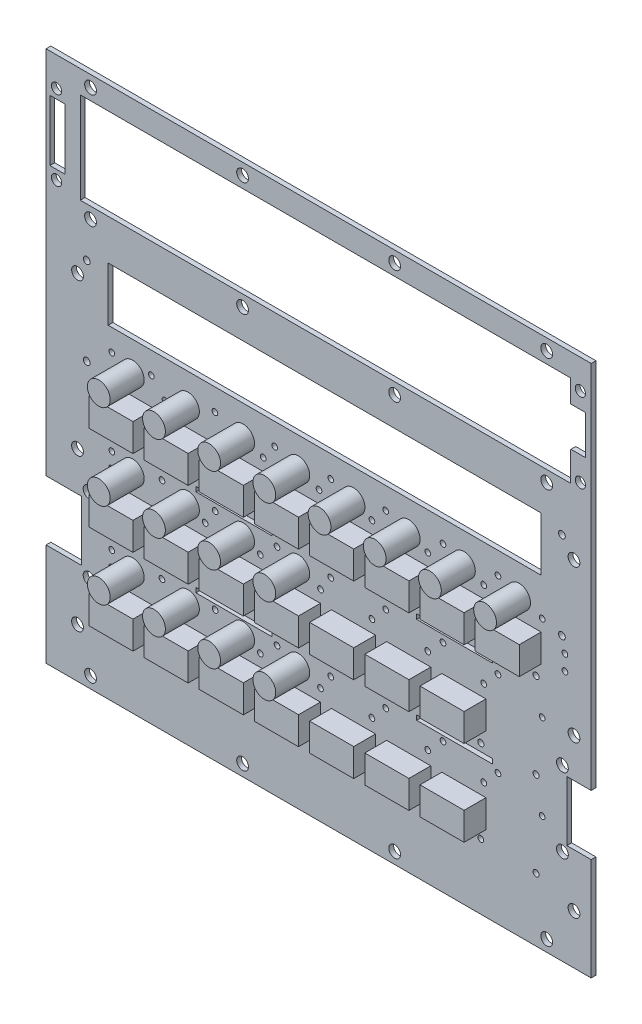
SolidWorks part; units mm, degrees
ref_plane "Front Plane" through (0, 0, 0) normal (0, 0, 1) x (1, 0, 0)
ref_plane "Top Plane" through (0, 0, 0) normal (0, 1, 0) x (1, 0, 0)
ref_plane "Right Plane" through (0, 0, 0) normal (1, 0, 0) x (0, 0, -1)
sketch "Sketch1" plane through (0, 0, 0) normal (0, 0, 1) x (1, 0, 0)
  line L0 (0, 0) -> (182.118, 0)
  line L1 (182.118, 0) -> (182.118, 34.2468)
  line L2 (182.118, 34.2468) -> (173.9875, 34.2468)
  line L3 (173.9875, 34.2468) -> (173.9875, 54.2468)
  line L4 (173.9875, 54.2468) -> (182.118, 54.2468)
  line L5 (182.118, 54.2468) -> (182.118, 177.8)
  line L6 (182.118, 177.8) -> (0, 177.8)
  line L7 (0, 177.8) -> (0, 54.2468)
  line L8 (0, 54.2468) -> (11.8694, 54.2468)
  line L9 (11.8694, 54.2468) -> (11.8694, 34.2468)
  line L10 (11.8694, 34.2468) -> (0, 34.2468)
  line L11 (0, 34.2468) -> (0, 0)
  line L12 (20.7391, 108.1786) -> (20.7391, 126.1796)
  line L13 (20.7391, 126.1796) -> (165.3007, 126.1796)
  line L14 (165.3007, 126.1796) -> (165.3007, 108.1786)
  line L15 (165.3007, 108.1786) -> (20.7391, 108.1786)
  line L16 (1.27, 144.653) -> (1.27, 164.973)
  line L17 (1.27, 164.973) -> (6.35, 164.973)
  line L18 (6.35, 164.973) -> (6.35, 144.653)
  line L19 (6.35, 144.653) -> (1.27, 144.653)
  line L20 (12.7, 170.18) -> (175.26, 170.18)
  line L21 (175.26, 170.18) -> (175.26, 162.6616)
  line L22 (175.26, 162.6616) -> (180.086, 162.6616)
  line L23 (180.086, 162.6616) -> (180.2892, 162.4584)
  line L24 (180.2892, 162.4584) -> (180.2892, 149.606)
  line L25 (180.2892, 149.606) -> (175.3616, 149.606)
  line L26 (175.3616, 149.606) -> (175.26, 149.5044)
  line L27 (175.26, 149.5044) -> (175.26, 139.7)
  line L28 (175.26, 139.7) -> (12.7, 139.7)
  line L29 (12.7, 139.7) -> (11.43, 139.7)
  line L30 (11.43, 139.7) -> (11.43, 170.18)
  line L31 (11.43, 170.18) -> (12.7, 170.18)
  line L32 (50.0634, 45.4152) -> (50.0634, 47.0027)
  line L33 (50.0634, 47.0027) -> (75.4634, 47.0027)
  line L34 (75.4634, 47.0027) -> (75.4634, 45.4152)
  line L35 (75.4634, 45.4152) -> (50.0634, 45.4152)
  line L36 (123.8134, 45.4152) -> (123.8134, 47.0027)
  line L37 (123.8134, 47.0027) -> (149.2134, 47.0027)
  line L38 (149.2134, 47.0027) -> (149.2134, 45.4152)
  line L39 (149.2134, 45.4152) -> (123.8134, 45.4152)
  line L40 (123.8134, 74.6252) -> (123.8134, 76.2127)
  line L41 (123.8134, 76.2127) -> (149.2134, 76.2127)
  line L42 (149.2134, 76.2127) -> (149.2134, 74.6252)
  line L43 (149.2134, 74.6252) -> (123.8134, 74.6252)
  line L44 (50.0634, 74.6252) -> (50.0634, 76.2127)
  line L45 (50.0634, 76.2127) -> (75.4634, 76.2127)
  line L46 (75.4634, 76.2127) -> (75.4634, 74.6252)
  line L47 (75.4634, 74.6252) -> (50.0634, 74.6252)
extrude "BOARD" add sketch "Sketch1" along normal blind 1.5921 separate body
ref_plane "Plane1" through (0, 0, 1.5921) normal (0, 0, 1) x (1, 0, 0)
sketch "Sketch11" plane through (0, 0, 1.5921) normal (0, 0, 1) x (1, 0, 0)
  circle A0 centre (84.2812, 41.1988) radius 3.81
extrude "LED-KINGBRIGHT_3P_2P54-10" add sketch "Sketch11" along normal blind 11.3538 separate body
sketch "Sketch12" plane through (0, 0, 1.5921) normal (0, 0, 1) x (1, 0, 0)
  circle A0 centre (65.8437, 41.1988) radius 3.81
extrude "LED-KINGBRIGHT_3P_2P54-11" add sketch "Sketch12" along normal blind 11.3538 separate body
sketch "Sketch13" plane through (0, 0, 1.5921) normal (0, 0, 1) x (1, 0, 0)
  circle A0 centre (47.4062, 41.1988) radius 3.81
extrude "LED-KINGBRIGHT_3P_2P54-12" add sketch "Sketch13" along normal blind 11.3538 separate body
sketch "Sketch14" plane through (0, 0, 1.5921) normal (0, 0, 1) x (1, 0, 0)
  circle A0 centre (28.9687, 41.1988) radius 3.81
extrude "LED-KINGBRIGHT_3P_2P54-13" add sketch "Sketch14" along normal blind 11.3538 separate body
sketch "Sketch15" plane through (0, 0, 1.5921) normal (0, 0, 1) x (1, 0, 0)
  circle A0 centre (84.2812, 69.7738) radius 3.81
extrude "LED-KINGBRIGHT_3P_2P54-14" add sketch "Sketch15" along normal blind 11.3538 separate body
sketch "Sketch16" plane through (0, 0, 1.5921) normal (0, 0, 1) x (1, 0, 0)
  circle A0 centre (65.8437, 69.7738) radius 3.81
extrude "LED-KINGBRIGHT_3P_2P54-15" add sketch "Sketch16" along normal blind 11.3538 separate body
sketch "Sketch17" plane through (0, 0, 1.5921) normal (0, 0, 1) x (1, 0, 0)
  circle A0 centre (47.4062, 69.7738) radius 3.81
extrude "LED-KINGBRIGHT_3P_2P54-16" add sketch "Sketch17" along normal blind 11.3538 separate body
sketch "Sketch18" plane through (0, 0, 1.5921) normal (0, 0, 1) x (1, 0, 0)
  circle A0 centre (28.9687, 69.7738) radius 3.81
extrude "LED-KINGBRIGHT_3P_2P54-17" add sketch "Sketch18" along normal blind 11.3538 separate body
sketch "Sketch19" plane through (0, 0, 1.5921) normal (0, 0, 1) x (1, 0, 0)
  circle A0 centre (158.0312, 98.3488) radius 3.81
extrude "LED-KINGBRIGHT_3P_2P54-18" add sketch "Sketch19" along normal blind 11.3538 separate body
sketch "Sketch20" plane through (0, 0, 1.5921) normal (0, 0, 1) x (1, 0, 0)
  circle A0 centre (139.5937, 98.3488) radius 3.81
extrude "LED-KINGBRIGHT_3P_2P54-19" add sketch "Sketch20" along normal blind 11.3538 separate body
sketch "Sketch21" plane through (0, 0, 1.5921) normal (0, 0, 1) x (1, 0, 0)
  circle A0 centre (121.1562, 98.3488) radius 3.81
extrude "LED-KINGBRIGHT_3P_2P54-20" add sketch "Sketch21" along normal blind 11.3538 separate body
sketch "Sketch22" plane through (0, 0, 1.5921) normal (0, 0, 1) x (1, 0, 0)
  circle A0 centre (102.7187, 98.3488) radius 3.81
extrude "LED-KINGBRIGHT_3P_2P54-21" add sketch "Sketch22" along normal blind 11.3538 separate body
sketch "Sketch23" plane through (0, 0, 1.5921) normal (0, 0, 1) x (1, 0, 0)
  circle A0 centre (84.2812, 98.3488) radius 3.81
extrude "LED-KINGBRIGHT_3P_2P54-22" add sketch "Sketch23" along normal blind 11.3538 separate body
sketch "Sketch24" plane through (0, 0, 1.5921) normal (0, 0, 1) x (1, 0, 0)
  circle A0 centre (65.8437, 98.3488) radius 3.81
extrude "LED-KINGBRIGHT_3P_2P54-23" add sketch "Sketch24" along normal blind 11.3538 separate body
sketch "Sketch25" plane through (0, 0, 1.5921) normal (0, 0, 1) x (1, 0, 0)
  circle A0 centre (47.4062, 98.3488) radius 3.81
extrude "LED-KINGBRIGHT_3P_2P54-24" add sketch "Sketch25" along normal blind 11.3538 separate body
sketch "Sketch26" plane through (0, 0, 1.5921) normal (0, 0, 1) x (1, 0, 0)
  circle A0 centre (28.9687, 98.3488) radius 3.81
extrude "LED-KINGBRIGHT_3P_2P54-25" add sketch "Sketch26" along normal blind 11.3538 separate body
sketch "Sketch29" plane through (0, 0, 1.5921) normal (0, 0, 1) x (1, 0, 0)
  line L0 (132.2277, 25.3238) -> (132.2277, 34.5948)
  line L1 (132.2277, 34.5948) -> (146.9597, 34.5948)
  line L2 (146.9597, 34.5948) -> (146.9597, 25.3238)
  line L3 (146.9597, 25.3238) -> (132.2277, 25.3238)
extrude "SWITCH-MCDTS2-3" add sketch "Sketch29" along normal blind 7.3 separate body
sketch "Sketch30" plane through (0, 0, 1.5921) normal (0, 0, 1) x (1, 0, 0)
  line L0 (113.7902, 25.3238) -> (113.7902, 34.5948)
  line L1 (113.7902, 34.5948) -> (128.5222, 34.5948)
  line L2 (128.5222, 34.5948) -> (128.5222, 25.3238)
  line L3 (128.5222, 25.3238) -> (113.7902, 25.3238)
extrude "SWITCH-MCDTS2-4" add sketch "Sketch30" along normal blind 7.3 separate body
sketch "Sketch31" plane through (0, 0, 1.5921) normal (0, 0, 1) x (1, 0, 0)
  line L0 (95.3527, 25.3238) -> (95.3527, 34.5948)
  line L1 (95.3527, 34.5948) -> (110.0847, 34.5948)
  line L2 (110.0847, 34.5948) -> (110.0847, 25.3238)
  line L3 (110.0847, 25.3238) -> (95.3527, 25.3238)
extrude "SWITCH-MCDTS2-5" add sketch "Sketch31" along normal blind 7.3 separate body
sketch "Sketch32" plane through (0, 0, 1.5921) normal (0, 0, 1) x (1, 0, 0)
  line L0 (76.9152, 25.3238) -> (76.9152, 34.5948)
  line L1 (76.9152, 34.5948) -> (91.6472, 34.5948)
  line L2 (91.6472, 34.5948) -> (91.6472, 25.3238)
  line L3 (91.6472, 25.3238) -> (76.9152, 25.3238)
extrude "SWITCH-MCDTS2-6" add sketch "Sketch32" along normal blind 7.3 separate body
sketch "Sketch33" plane through (0, 0, 1.5921) normal (0, 0, 1) x (1, 0, 0)
  line L0 (58.4777, 25.3238) -> (58.4777, 34.5948)
  line L1 (58.4777, 34.5948) -> (73.2097, 34.5948)
  line L2 (73.2097, 34.5948) -> (73.2097, 25.3238)
  line L3 (73.2097, 25.3238) -> (58.4777, 25.3238)
extrude "SWITCH-MCDTS2-7" add sketch "Sketch33" along normal blind 7.3 separate body
sketch "Sketch34" plane through (0, 0, 1.5921) normal (0, 0, 1) x (1, 0, 0)
  line L0 (40.0402, 25.3238) -> (40.0402, 34.5948)
  line L1 (40.0402, 34.5948) -> (54.7722, 34.5948)
  line L2 (54.7722, 34.5948) -> (54.7722, 25.3238)
  line L3 (54.7722, 25.3238) -> (40.0402, 25.3238)
extrude "SWITCH-MCDTS2-8" add sketch "Sketch34" along normal blind 7.3 separate body
sketch "Sketch35" plane through (0, 0, 1.5921) normal (0, 0, 1) x (1, 0, 0)
  line L0 (21.6027, 25.3238) -> (21.6027, 34.5948)
  line L1 (21.6027, 34.5948) -> (36.3347, 34.5948)
  line L2 (36.3347, 34.5948) -> (36.3347, 25.3238)
  line L3 (36.3347, 25.3238) -> (21.6027, 25.3238)
extrude "SWITCH-MCDTS2-9" add sketch "Sketch35" along normal blind 7.3 separate body
sketch "Sketch36" plane through (0, 0, 1.5921) normal (0, 0, 1) x (1, 0, 0)
  line L0 (132.2277, 53.8988) -> (132.2277, 63.1698)
  line L1 (132.2277, 63.1698) -> (146.9597, 63.1698)
  line L2 (146.9597, 63.1698) -> (146.9597, 53.8988)
  line L3 (146.9597, 53.8988) -> (132.2277, 53.8988)
extrude "SWITCH-MCDTS2-10" add sketch "Sketch36" along normal blind 7.3 separate body
sketch "Sketch37" plane through (0, 0, 1.5921) normal (0, 0, 1) x (1, 0, 0)
  line L0 (113.7902, 53.8988) -> (113.7902, 63.1698)
  line L1 (113.7902, 63.1698) -> (128.5222, 63.1698)
  line L2 (128.5222, 63.1698) -> (128.5222, 53.8988)
  line L3 (128.5222, 53.8988) -> (113.7902, 53.8988)
extrude "SWITCH-MCDTS2-11" add sketch "Sketch37" along normal blind 7.3 separate body
sketch "Sketch38" plane through (0, 0, 1.5921) normal (0, 0, 1) x (1, 0, 0)
  line L0 (95.3527, 53.8988) -> (95.3527, 63.1698)
  line L1 (95.3527, 63.1698) -> (110.0847, 63.1698)
  line L2 (110.0847, 63.1698) -> (110.0847, 53.8988)
  line L3 (110.0847, 53.8988) -> (95.3527, 53.8988)
extrude "SWITCH-MCDTS2-12" add sketch "Sketch38" along normal blind 7.3 separate body
sketch "Sketch39" plane through (0, 0, 1.5921) normal (0, 0, 1) x (1, 0, 0)
  line L0 (76.9152, 53.8988) -> (76.9152, 63.1698)
  line L1 (76.9152, 63.1698) -> (91.6472, 63.1698)
  line L2 (91.6472, 63.1698) -> (91.6472, 53.8988)
  line L3 (91.6472, 53.8988) -> (76.9152, 53.8988)
extrude "SWITCH-MCDTS2-13" add sketch "Sketch39" along normal blind 7.3 separate body
sketch "Sketch40" plane through (0, 0, 1.5921) normal (0, 0, 1) x (1, 0, 0)
  line L0 (58.4777, 53.8988) -> (58.4777, 63.1698)
  line L1 (58.4777, 63.1698) -> (73.2097, 63.1698)
  line L2 (73.2097, 63.1698) -> (73.2097, 53.8988)
  line L3 (73.2097, 53.8988) -> (58.4777, 53.8988)
extrude "SWITCH-MCDTS2-14" add sketch "Sketch40" along normal blind 7.3 separate body
sketch "Sketch41" plane through (0, 0, 1.5921) normal (0, 0, 1) x (1, 0, 0)
  line L0 (40.0402, 53.8988) -> (40.0402, 63.1698)
  line L1 (40.0402, 63.1698) -> (54.7722, 63.1698)
  line L2 (54.7722, 63.1698) -> (54.7722, 53.8988)
  line L3 (54.7722, 53.8988) -> (40.0402, 53.8988)
extrude "SWITCH-MCDTS2-15" add sketch "Sketch41" along normal blind 7.3 separate body
sketch "Sketch42" plane through (0, 0, 1.5921) normal (0, 0, 1) x (1, 0, 0)
  line L0 (21.6027, 53.8988) -> (21.6027, 63.1698)
  line L1 (21.6027, 63.1698) -> (36.3347, 63.1698)
  line L2 (36.3347, 63.1698) -> (36.3347, 53.8988)
  line L3 (36.3347, 53.8988) -> (21.6027, 53.8988)
extrude "SWITCH-MCDTS2-16" add sketch "Sketch42" along normal blind 7.3 separate body
sketch "Sketch43" plane through (0, 0, 1.5921) normal (0, 0, 1) x (1, 0, 0)
  line L0 (150.6652, 82.4738) -> (150.6652, 91.7448)
  line L1 (150.6652, 91.7448) -> (165.3972, 91.7448)
  line L2 (165.3972, 91.7448) -> (165.3972, 82.4738)
  line L3 (165.3972, 82.4738) -> (150.6652, 82.4738)
extrude "SWITCH-MCDTS2-17" add sketch "Sketch43" along normal blind 7.3 separate body
sketch "Sketch44" plane through (0, 0, 1.5921) normal (0, 0, 1) x (1, 0, 0)
  line L0 (132.2277, 82.4738) -> (132.2277, 91.7448)
  line L1 (132.2277, 91.7448) -> (146.9597, 91.7448)
  line L2 (146.9597, 91.7448) -> (146.9597, 82.4738)
  line L3 (146.9597, 82.4738) -> (132.2277, 82.4738)
extrude "SWITCH-MCDTS2-18" add sketch "Sketch44" along normal blind 7.3 separate body
sketch "Sketch45" plane through (0, 0, 1.5921) normal (0, 0, 1) x (1, 0, 0)
  line L0 (113.7902, 82.4738) -> (113.7902, 91.7448)
  line L1 (113.7902, 91.7448) -> (128.5222, 91.7448)
  line L2 (128.5222, 91.7448) -> (128.5222, 82.4738)
  line L3 (128.5222, 82.4738) -> (113.7902, 82.4738)
extrude "SWITCH-MCDTS2-19" add sketch "Sketch45" along normal blind 7.3 separate body
sketch "Sketch46" plane through (0, 0, 1.5921) normal (0, 0, 1) x (1, 0, 0)
  line L0 (95.3527, 82.4738) -> (95.3527, 91.7448)
  line L1 (95.3527, 91.7448) -> (110.0847, 91.7448)
  line L2 (110.0847, 91.7448) -> (110.0847, 82.4738)
  line L3 (110.0847, 82.4738) -> (95.3527, 82.4738)
extrude "SWITCH-MCDTS2-20" add sketch "Sketch46" along normal blind 7.3 separate body
sketch "Sketch47" plane through (0, 0, 1.5921) normal (0, 0, 1) x (1, 0, 0)
  line L0 (76.9152, 82.4738) -> (76.9152, 91.7448)
  line L1 (76.9152, 91.7448) -> (91.6472, 91.7448)
  line L2 (91.6472, 91.7448) -> (91.6472, 82.4738)
  line L3 (91.6472, 82.4738) -> (76.9152, 82.4738)
extrude "SWITCH-MCDTS2-21" add sketch "Sketch47" along normal blind 7.3 separate body
sketch "Sketch48" plane through (0, 0, 1.5921) normal (0, 0, 1) x (1, 0, 0)
  line L0 (58.4777, 82.4738) -> (58.4777, 91.7448)
  line L1 (58.4777, 91.7448) -> (73.2097, 91.7448)
  line L2 (73.2097, 91.7448) -> (73.2097, 82.4738)
  line L3 (73.2097, 82.4738) -> (58.4777, 82.4738)
extrude "SWITCH-MCDTS2-22" add sketch "Sketch48" along normal blind 7.3 separate body
sketch "Sketch49" plane through (0, 0, 1.5921) normal (0, 0, 1) x (1, 0, 0)
  line L0 (40.0402, 82.4738) -> (40.0402, 91.7448)
  line L1 (40.0402, 91.7448) -> (54.7722, 91.7448)
  line L2 (54.7722, 91.7448) -> (54.7722, 82.4738)
  line L3 (54.7722, 82.4738) -> (40.0402, 82.4738)
extrude "SWITCH-MCDTS2-23" add sketch "Sketch49" along normal blind 7.3 separate body
sketch "Sketch50" plane through (0, 0, 1.5921) normal (0, 0, 1) x (1, 0, 0)
  line L0 (21.6027, 82.4738) -> (21.6027, 91.7448)
  line L1 (21.6027, 91.7448) -> (36.3347, 91.7448)
  line L2 (36.3347, 91.7448) -> (36.3347, 82.4738)
  line L3 (36.3347, 82.4738) -> (21.6027, 82.4738)
extrude "SWITCH-MCDTS2-24" add sketch "Sketch50" along normal blind 7.3 separate body
sketch "Sketch56" plane through (0, 0, 1.5921) normal (0, 0, 1) x (1, 0, 0)
  circle B0 centre (163.703, 21.1074) radius 1.016
  circle B1 centre (163.703, 49.6824) radius 1.016
  circle B2 centre (145.2626, 21.8186) radius 0.9652
  circle B3 centre (126.8476, 21.6154) radius 0.9652
  circle B4 centre (108.4072, 21.7424) radius 0.9652
  circle B5 centre (89.9668, 21.844) radius 0.9652
  circle B6 centre (71.5264, 20.7772) radius 0.9652
  circle B7 centre (53.086, 21.1582) radius 0.9652
  circle B8 centre (34.6472, 21.1328) radius 1.016
  circle B9 centre (145.2626, 49.5554) radius 1.016
  circle B10 centre (126.8222, 49.3522) radius 1.016
  circle B11 centre (108.3818, 49.1236) radius 1.016
  circle B12 centre (89.9414, 49.6824) radius 1.016
  circle B13 centre (71.501, 49.1998) radius 1.016
  circle B14 centre (53.0606, 49.1998) radius 1.016
  circle B15 centre (34.6202, 49.276) radius 1.016
  circle B16 centre (163.703, 78.2574) radius 1.016
  circle B17 centre (145.2626, 77.7748) radius 1.016
  circle B18 centre (126.746, 78.3336) radius 1.016
  circle B19 centre (108.3818, 78.74) radius 1.016
  circle B20 centre (89.9414, 78.3336) radius 1.016
  circle B21 centre (71.501, 78.2574) radius 1.016
  circle B22 centre (53.0606, 78.4098) radius 1.016
  circle B23 centre (34.6202, 78.0542) radius 1.016
  circle B24 centre (91.694, 38.6588) radius 0.9525
  circle B25 centre (77.1652, 43.7388) radius 0.9525
  circle B26 centre (71.5772, 38.6588) radius 0.9525
  circle B27 centre (56.4896, 43.7388) radius 0.9525
  circle B28 centre (38.735, 43.7388) radius 0.9525
  circle B29 centre (21.8948, 38.6588) radius 0.9525
  circle B30 centre (21.971, 43.7388) radius 0.9525
  circle B31 centre (77.1652, 72.3138) radius 0.9525
  circle B32 centre (91.694, 67.2338) radius 0.9525
  circle B33 centre (71.5772, 67.2338) radius 0.9525
  circle B34 centre (56.4896, 72.3138) radius 0.9525
  circle B35 centre (53.1368, 67.2338) radius 0.9525
  circle B36 centre (38.735, 72.3138) radius 0.9525
  circle B37 centre (21.8948, 67.2338) radius 0.9525
  circle B38 centre (21.971, 72.3138) radius 0.9525
  circle B39 centre (165.735, 95.8088) radius 0.9525
  circle B40 centre (150.9776, 100.8888) radius 0.9525
  circle B41 centre (146.2278, 95.8088) radius 0.9525
  circle B42 centre (132.6134, 100.8888) radius 0.9525
  circle B43 centre (113.4872, 100.8888) radius 0.9525
  circle B44 centre (127.508, 95.8088) radius 0.9525
  circle B45 centre (108.8644, 95.8088) radius 0.9525
  circle B46 centre (95.0976, 100.8888) radius 0.9525
  circle B47 centre (91.186, 95.8088) radius 0.9525
  circle B48 centre (76.3778, 100.8888) radius 0.9525
  circle B49 centre (72.5424, 95.8088) radius 0.9525
  circle B50 centre (56.4134, 100.8888) radius 0.9525
  circle B51 centre (39.7256, 95.8088) radius 0.9525
  circle B52 centre (35.179, 100.8888) radius 0.9525
  circle B53 centre (24.2062, 95.8088) radius 0.9525
  circle B54 centre (21.971, 100.8888) radius 0.9525
  circle B55 centre (132.6134, 72.3138) radius 0.9525
  circle B56 centre (146.2278, 67.2338) radius 0.9525
  circle B57 centre (113.4872, 72.3138) radius 0.9525
  circle B58 centre (127.508, 67.2338) radius 0.9525
  circle B59 centre (95.0976, 72.3138) radius 0.9525
  circle B60 centre (108.8644, 67.2338) radius 0.9525
  circle B61 centre (150.9776, 43.7388) radius 0.9525
  circle B62 centre (132.6134, 43.7388) radius 0.9525
  circle B63 centre (113.4872, 43.7388) radius 0.9525
  circle B64 centre (95.0976, 43.7388) radius 0.9525
  circle B65 centre (108.8644, 38.6588) radius 0.9525
  circle B66 centre (150.9776, 72.3138) radius 0.9525
  circle B67 centre (165.735, 67.2338) radius 0.9525
  circle B68 centre (173.3296, 89.4588) radius 0.9525
  circle B69 centre (173.355, 84.3534) radius 0.9525
  circle B70 centre (176.3725, 118.11) radius 1.9685
  circle B71 centre (176.3725, 67.31) radius 1.9685
  circle B72 centre (176.3725, 16.51) radius 1.9685
  circle B73 centre (167.259, 135.89) radius 1.9685
  circle B74 centre (116.459, 135.89) radius 1.9685
  circle B75 centre (65.659, 135.89) radius 1.9685
  circle B76 centre (14.859, 135.89) radius 1.9685
  circle B77 centre (10.5105, 118.11) radius 1.9685
  circle B78 centre (10.5105, 67.31) radius 1.9685
  circle B79 centre (10.5105, 16.51) radius 1.9685
  circle B80 centre (165.735, 38.6588) radius 0.9525
  circle B81 centre (146.2278, 38.6588) radius 0.9525
  circle B82 centre (127.508, 38.6588) radius 0.9525
  circle B83 centre (14.859, 173.99) radius 1.9685
  circle B84 centre (65.659, 173.99) radius 1.9685
  circle B85 centre (116.459, 173.99) radius 1.9685
  circle B86 centre (167.259, 173.99) radius 1.9685
  circle B87 centre (167.259, 3.81) radius 1.9685
  circle B88 centre (116.459, 3.81) radius 1.9685
  circle B89 centre (65.659, 3.81) radius 1.9685
  circle B90 centre (14.859, 3.81) radius 1.9685
  circle B91 centre (172.5066, 56.7436) radius 1.9685
  circle B92 centre (172.5066, 31.75) radius 1.9685
  circle B93 centre (14.3688, 56.7436) radius 1.9685
  circle B94 centre (14.3688, 31.75) radius 1.9685
  circle B95 centre (172.3415, 123.3754) radius 1.1303
  circle B96 centre (172.3415, 94.1654) radius 1.1303
  circle B97 centre (13.5915, 94.1654) radius 1.1303
  circle B98 centre (13.5915, 123.3754) radius 1.1303
  circle B99 centre (178.5137, 141.5618) radius 1.7145
  circle B100 centre (178.5137, 168.0616) radius 1.7145
  circle B101 centre (3.5001, 168.0616) radius 1.7145
  circle B102 centre (3.5001, 141.5618) radius 1.7145
sketch_block_instance "Block-Model-1"
sketch_block "Block-Model"
extrude "Cut-Extrude1" cut sketch "Sketch56" against normal blind 10
